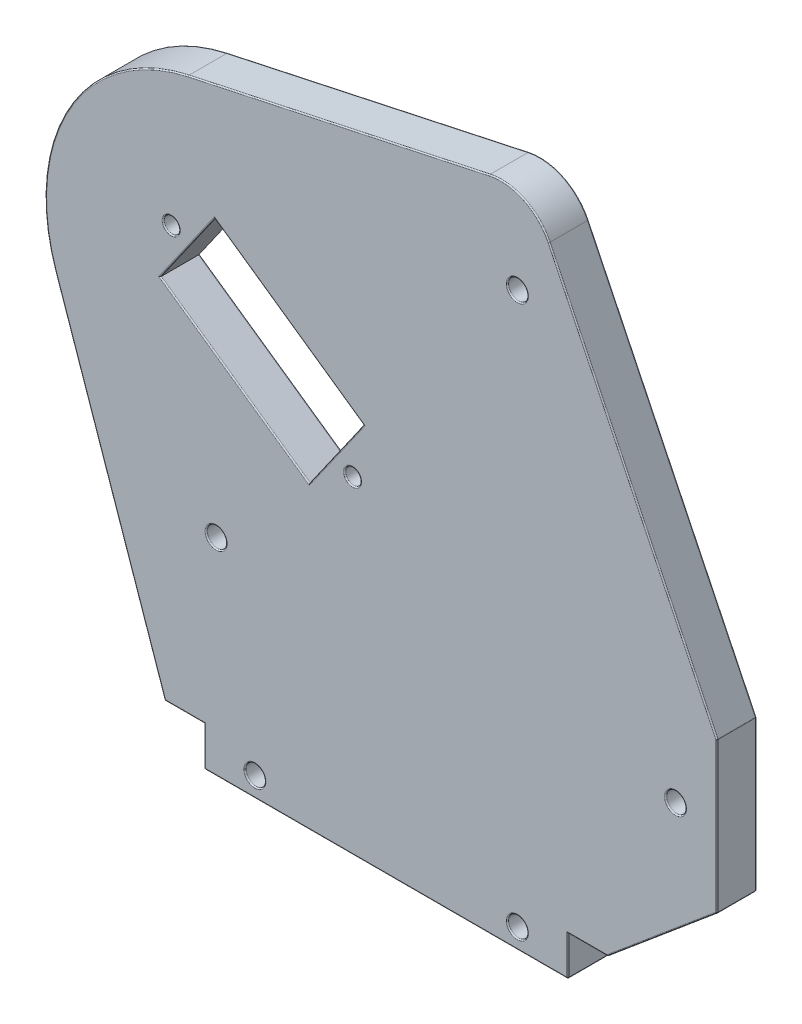
SolidWorks part; units mm, degrees
ref_plane "前视基准面" through (0, 0, 0) normal (0, 0, 1) x (1, 0, 0)
ref_plane "上视基准面" through (0, 0, 0) normal (0, 1, 0) x (1, 0, 0)
ref_plane "右视基准面" through (0, 0, 0) normal (1, 0, 0) x (0, 0, -1)
sketch "草图1" plane through (0, 0, 0) normal (0, 0, 1) x (1, 0, 0)
  line L0 (-25.0297, 79.9436) -> (13.0723, 88.1382) construction
  line L1 (41.85, 40.6215) -> (20.6106, 84.4605) construction
  line L2 (41.85, 21.6215) -> (41.85, 40.6215) construction
  line L3 (28, 10) -> (41.85, 21.6215) construction
  line L4 (23, 10) -> (28, 10) construction
  line L5 (23, 0) -> (23, 10) construction
  line L6 (-23, 0) -> (23, 0) construction
  line L7 (-23, 10) -> (-28, 10) construction
  line L8 (-23, 0) -> (-23, 10) construction
  line L9 (-28, 10) -> (-41.8438, 50.1182) construction
  line L10 (-25.0297, 79.9436) -> (13.0723, 88.1382)
  line L11 (41.85, 40.6215) -> (20.6106, 84.4605)
  line L12 (41.85, 21.6215) -> (41.85, 40.6215)
  line L13 (28, 10) -> (41.85, 21.6215)
  line L14 (23, 10) -> (28, 10)
  line L15 (23, 0) -> (23, 10)
  line L16 (-23, 0) -> (23, 0)
  line L17 (-23, 10) -> (-28, 10)
  line L18 (-23, 0) -> (-23, 10)
  line L19 (-28, 10) -> (-41.8438, 50.1182)
  line L20 (0, 0) -> (0, 21.6215) construction
  line L21 (-28.5764, 56.1065) -> (-21.6935, 65.9364)
  line L22 (-28.5764, 56.1065) -> (-9.7359, 42.9143)
  line L23 (-21.6935, 65.9364) -> (-2.853, 52.7441)
  line L24 (-9.7359, 42.9143) -> (-2.853, 52.7441)
  line L25 (-6.2944, 47.8292) -> (-25.1349, 61.0215) construction
  line L26 (-15.7147, 54.4253) -> (-19.1561, 49.5104) construction
  arc A0 (20.6106, 84.4605) -> (13.0723, 88.1382) centre (14.5, 81.5) ccw construction
  arc A1 (-25.0297, 79.9436) -> (-41.8438, 50.1182) centre (-20.22, 57.58) ccw construction
  arc A2 (20.6106, 84.4605) -> (13.0723, 88.1382) centre (14.5, 81.5) ccw
  arc A3 (-25.0297, 79.9436) -> (-41.8438, 50.1182) centre (-20.22, 57.58) ccw
  circle A4 centre (-27.1828, 62.4554) radius 1
  circle A5 centre (-4.2465, 46.3953) radius 1
  point P6 (-16.6, 7.5)
  point P7 (16.6, 7.5)
  point P9 (36.6, 31.1215)
  point P11 (-21.5, 31.1215)
  point P13 (16.6, 77.2733)
  point P17 (41.85, 31.1215)
  dimension "D9" = 2
  dimension "D1" = 5.25
  dimension "D2" = 7.5
  dimension "D3" = 21.5
  dimension "D4" = 23
  dimension "D5" = 12
  dimension "D6" = 35
  dimension "D7" = 6
  dimension "D8" = 2.5
  dimension "D10" = 6.4
extrude "凸台-拉伸1" add sketch "草图1" along normal blind 5
hole_wizard "M3 螺纹孔的螺纹孔钻头1" positions "草图2" profile "草图3" hole size "M3" standard "ISO" end condition through all
sketch "草图2" plane through (0, 0, 5) normal (0, 0, 1) x (1, 0, 0)
  point P0 (16.6, 77.2733)
  point P3 (36.6, 31.1215)
  point P6 (16.6, 7.5)
  point P9 (-16.6, 7.5)
  point P12 (-21.5, 31.1215)
sketch "草图3" plane through (16.6, 77.2733, 5) normal (1, 0, 0) x (0, -1, 0)
  line L0 (0, 0) -> (0, 5)
  line L1 (0, 5) -> (1.25, 5)
  line L2 (1.25, 5) -> (1.25, 0)
  line L5 (1.25, 0) -> (0, 0)
  line L11 (0, -6.35) -> (0, 107.95) construction
  dimension "通孔孔直径" = 2.5
  dimension "通孔孔深度" = 5
fillet "圆角1" radius 0.15 52 edges at (17.85, 77.2733, 5) (17.85, 77.2733, 0) (37.85, 31.1215, 5) (37.85, 31.1215, 0) (17.85, 7.5, 5) (17.85, 7.5, 0) (-15.35, 7.5, 5) (-15.35, 7.5, 0) (-20.25, 31.1215, 5) (-20.25, 31.1215, 0) (-5.2465, 46.3953, 0) (-5.2465, 46.3953, 5) (-26.1828, 62.4554, 0) (-26.1828, 62.4554, 5) (-19.1561, 49.5104, 0) (-6.2944, 47.8292, 0) (-12.2732, 59.3402, 0) (-25.1349, 61.0215, 0) (-19.1561, 49.5104, 5) (-6.2944, 47.8292, 5) (-12.2732, 59.3402, 5) (-25.1349, 61.0215, 5) (17.4772, 87.6025, 0) (-5.9787, 84.0409, 0) (-40.1467, 68.8136, 0) (-34.9219, 30.0591, 0) (-25.5, 10, 0) (-23, 5, 0) (0, 0, 0) (23, 5, 0) (25.5, 10, 0) (34.925, 15.8108, 0) (41.85, 31.1215, 0) (31.2303, 62.541, 0) (17.4772, 87.6025, 5) (-5.9787, 84.0409, 5) (-40.1467, 68.8136, 5) (-34.9219, 30.0591, 5) (-25.5, 10, 5) (0, 0, 5) (23, 5, 5) (25.5, 10, 5) (34.925, 15.8108, 5) (41.85, 31.1215, 5) (31.2303, 62.541, 5) (41.85, 40.6215, 2.5) (41.85, 21.6215, 2.5) (28, 10, 2.5) (23, 0, 2.5) (-28, 10, 2.5) (-23, 5, 5) (-23, 0, 2.5)
sketch "草图4" plane through (0, 0, 0) normal (0, 0, -1) x (-1, 0, 0)
  line L0 (23, 10) -> (23, 0.15) construction
  line L1 (-23, 0) -> (23, 0)
  line L2 (-23, 0) -> (-23, 5)
  line L3 (-23, 5) -> (23, 5)
  line L4 (23, 0) -> (23, 5)
  line L5 (22.85, 0) -> (-22.85, 0) construction
  line L7 (-23, 10) -> (-23, 0.15) construction
  dimension "D1" = 5
extrude "切除-拉伸1" cut sketch "草图4" against normal through all
fillet "圆角2" radius 0.15 8 edges at (23, 5, 2.5) (22.9561, 5, 0.0439) (0, 5, 0) (-22.9561, 5, 0.0439) (-23, 5, 2.5) (-22.9561, 5, 4.9561) (0, 5, 5) (22.9561, 5, 4.9561)
